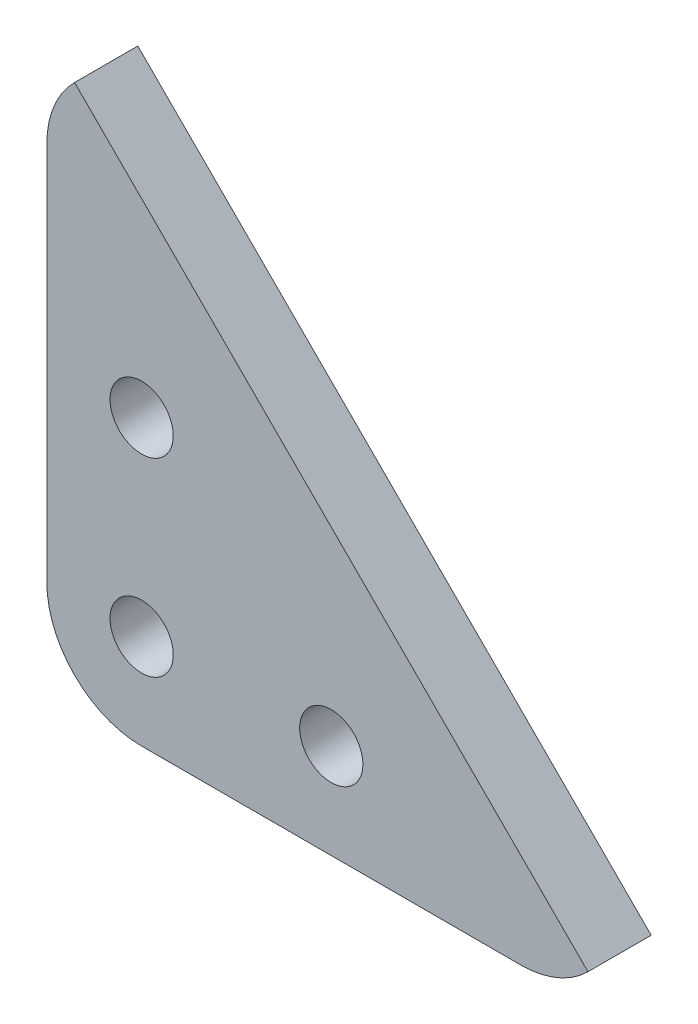
SolidWorks part; units mm, degrees
ref_plane "Alzado" through (0, 0, 0) normal (0, 0, 1) x (1, 0, 0)
ref_plane "Planta" through (0, 0, 0) normal (0, 1, 0) x (1, 0, 0)
ref_plane "Vista lateral" through (0, 0, 0) normal (1, 0, 0) x (0, 0, -1)
sketch "Model" plane through (0, 0, 0) normal (0, 0, 1) x (1, 0, 0)
  line L0 (-105.9434, 101.0565) -> (-105.9434, 83.0565)
  line L1 (-101.4434, 78.5565) -> (-83.4434, 78.5565)
  line L2 (-104.6254, 104.2385) -> (-80.2614, 79.8746)
  circle A0 centre (-101.4434, 92.0565) radius 1.5
  circle A1 centre (-101.4434, 83.0565) radius 1.5
  circle A2 centre (-92.4434, 83.0565) radius 1.5
  arc A3 (-104.6254, 104.2385) -> (-105.9434, 101.0565) centre (-101.4434, 101.0565) ccw
  arc A4 (-105.9434, 83.0565) -> (-101.4434, 78.5565) centre (-101.4434, 83.0565) ccw
  arc A5 (-83.4434, 78.5565) -> (-80.2614, 79.8746) centre (-83.4434, 83.0565) ccw
extrude "Saliente-Extruir1" add sketch "Model" along normal blind 3
